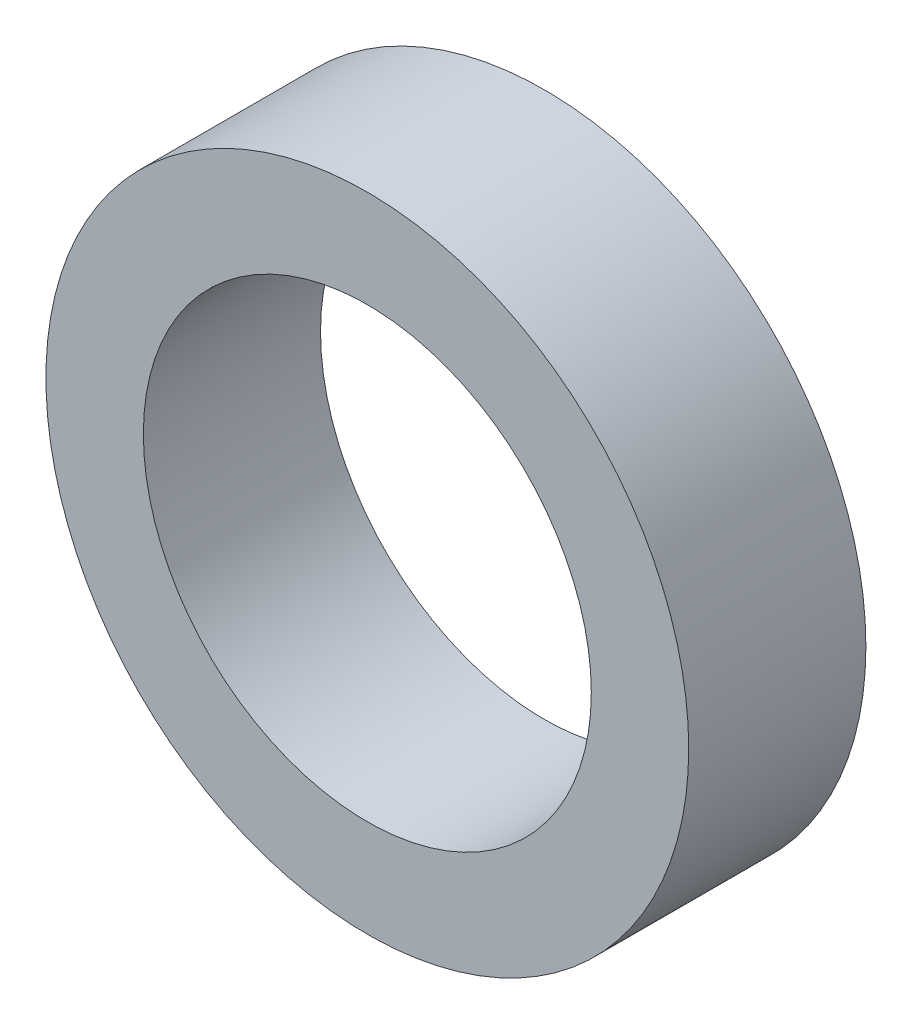
SolidWorks part; units mm, degrees
ref_plane "Спереди" through (0, 0, 0) normal (0, 0, 1) x (1, 0, 0)
ref_plane "Сверху" through (0, 0, 0) normal (0, 1, 0) x (1, 0, 0)
ref_plane "Справа" through (0, 0, 0) normal (1, 0, 0) x (0, 0, -1)
sketch "Эскиз1" plane through (0, 0, 0) normal (0, 0, 1) x (1, 0, 0)
  circle A0 centre (0, 0) radius 127
  circle A1 centre (0, 0) radius 88.5
extrude "Tire_reference" add sketch "Эскиз1" along normal blind 70 from offset 35
